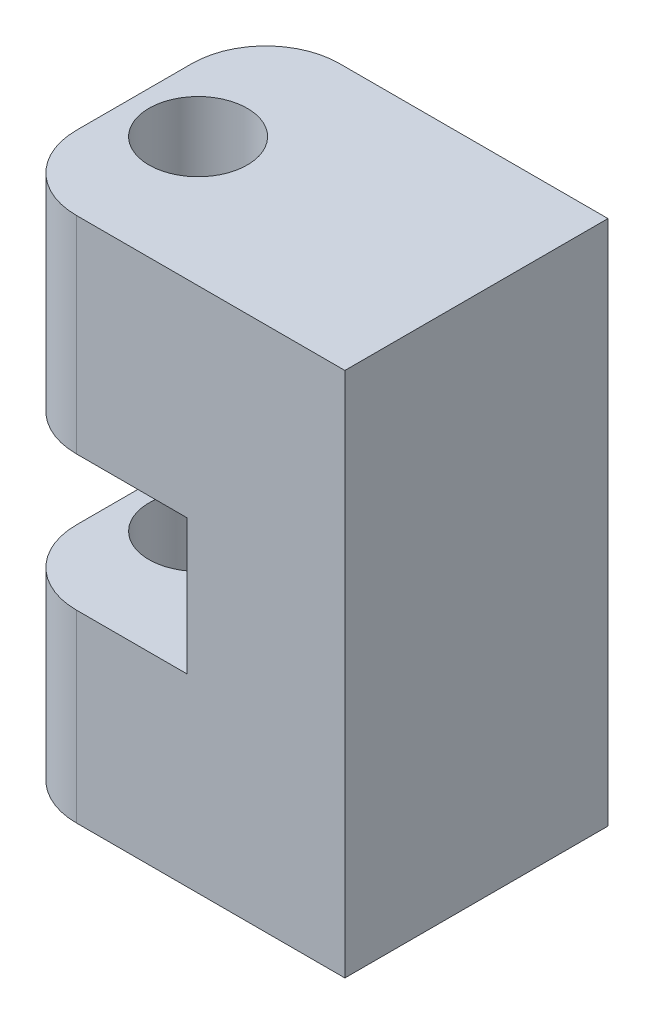
SolidWorks part; units mm, degrees
ref_plane "Front" through (0, 0, 0) normal (0, 0, 1) x (1, 0, 0)
ref_plane "Top" through (0, 0, 0) normal (0, 1, 0) x (1, 0, 0)
ref_plane "Right" through (0, 0, 0) normal (1, 0, 0) x (0, 0, -1)
sketch "Sketch1" plane through (0, 0, 0) normal (0, 1, 0) x (1, 0, 0)
  line L0 (0, 9.3172) -> (0, 9.1678) construction
  line L1 (0, 0) -> (20.32, 0)
  line L2 (0, 0) -> (0, 12.7)
  line L3 (0, 12.7) -> (20.32, 12.7)
  line L4 (20.32, 0) -> (20.32, 12.7)
  line L5 (0.0894, 9.3172) -> (0.0894, 9.1678)
  line L6 (-0.0894, 9.3172) -> (-0.0894, 9.1678)
  line L7 (0, 7.6957) -> (0, 5.0493) construction
  line L10 (5.1, 7.6957) -> (5.1, 5.0493)
  line L11 (-5.1, 7.6957) -> (-5.1, 5.0493)
  arc A0 (0.0894, 9.3172) -> (-0.0894, 9.3172) centre (0, 9.3172) ccw
  arc A1 (-0.0894, 9.1678) -> (0.0894, 9.1678) centre (0, 9.1678) ccw
  arc A4 (5.1, 7.6957) -> (-5.1, 7.6957) centre (0, 7.6957) ccw
  arc A5 (-5.1, 5.0493) -> (5.1, 5.0493) centre (0, 5.0493) ccw
  point P7 (0, 9.2425)
  point P14 (0, 6.3725)
  dimension "D1" = 20.32
  dimension "D2" = 12.7
extrude "Boss-Extrude4" add sketch "Sketch1" along normal blind 25.4 contours L11 A5 L1 L2 A1 L6 A0 L3 A4 | L1 A5 L10 A4 L3 L2 A0 L5 A1 | A5 L1 L4 L3 A4 L10
sketch "Sketch3" plane through (0, 25.4, 0) normal (0, 1, 0) x (1, 0, 0)
  circle A0 centre (0, 6.1634) radius 2
  dimension "D1" = 4
extrude "Cut-Extrude1" cut sketch "Sketch3" against normal blind 25.4 contours A0
sketch "Sketch5" plane through (20.32, 0, 0) normal (1, 0, 0) x (0, 0, -1)
  line L1 (38.2751, 38.8271) -> (-16.024, 38.8271)
  line L2 (38.2751, 38.8271) -> (38.2751, -55.3885)
  line L3 (38.2751, -55.3885) -> (-16.024, -55.3885)
  line L4 (-16.024, 38.8271) -> (-16.024, -55.3885)
extrude "Cut-Extrude2" cut sketch "Sketch5" against normal blind 4.5
sketch "Sketch7" plane through (-5.1, 0, 0) normal (-1, 0, 0) x (0, 0, 1)
  line L0 (-7.6957, 25.4) -> (-5.0493, 25.4) construction
  line L1 (-15.6651, 15) -> (3.0281, 15)
  line L2 (-15.6651, 15) -> (-15.6651, 9.5)
  line L3 (-15.6651, 9.5) -> (3.0281, 9.5)
  line L4 (3.0281, 15) -> (3.0281, 9.5)
  dimension "D1" = 5.5
  dimension "D2" = 10.4
extrude "Cut-Extrude3" cut sketch "Sketch7" against normal blind 14.5
sketch "Sketch9" plane through (0, 0, -12.7) normal (0, 0, -1) x (-1, 0, 0)
  line L1 (-22.5674, 28.7595) -> (13.5442, 28.7595)
  line L2 (-22.5674, 28.7595) -> (-22.5674, -4.4046)
  line L3 (-22.5674, -4.4046) -> (13.5442, -4.4046)
  line L4 (13.5442, 28.7595) -> (13.5442, -4.4046)
extrude "Cut-Extrude4" cut sketch "Sketch9" against normal blind 1
sketch "Sketch10" plane through (0, 0, 0) normal (0, 0, 1) x (1, 0, 0)
  line L1 (-28.2632, -7.6451) -> (34.5285, -7.6451)
  line L2 (-28.2632, -7.6451) -> (-28.2632, 29.5981)
  line L3 (-28.2632, 29.5981) -> (34.5285, 29.5981)
  line L4 (34.5285, -7.6451) -> (34.5285, 29.5981)
extrude "Cut-Extrude6" cut sketch "Sketch10" against normal blind 1
fillet "Fillet2" radius 3 4 edges at (-3.1005, 4.75, -1) (-3.1005, 20.2, -1) (-3.1585, 20.2, -11.7) (-3.1585, 4.75, -11.7)
sketch "Sketch11" plane through (9.4, 0, 0) normal (-1, 0, 0) x (0, 0, 1)
  line L1 (-11.7, 9.5) -> (-1, 9.5)
  line L2 (-11.7, 9.5) -> (-11.7, 15)
  line L3 (-11.7, 15) -> (-1, 15)
  line L4 (-1, 9.5) -> (-1, 15)
extrude "Boss-Extrude5" add sketch "Sketch11" along normal blind 2
sketch "Sketch12" plane through (-5.1, 0, 0) normal (-1, 0, 0) x (0, 0, 1)
  line L1 (-13.4183, -11.6019) -> (0, -11.6019)
  line L2 (-13.4183, -11.6019) -> (-13.4183, 44.9502)
  line L3 (-13.4183, 44.9502) -> (0, 44.9502)
  line L4 (0, -11.6019) -> (0, 44.9502)
extrude "Cut-Extrude7" cut sketch "Sketch12" against normal blind 10
sketch "Sketch14" plane through (7.4, 0, 0) normal (-1, 0, 0) x (0, 0, 1)
  line L1 (-11.7, 9.5) -> (-1, 9.5)
  line L2 (-11.7, 9.5) -> (-11.7, 15)
  line L3 (-11.7, 15) -> (-1, 15)
  line L4 (-1, 9.5) -> (-1, 15)
extrude "Boss-Extrude7" add sketch "Sketch14" along normal blind 2
sketch "Sketch15" plane through (4.9, 0, 0) normal (-1, 0, 0) x (0, 0, 1)
  line L1 (-11.7, 0) -> (-1, 0)
  line L2 (-11.7, 0) -> (-11.7, 9.5)
  line L3 (-11.7, 9.5) -> (-1, 9.5)
  line L4 (-1, 0) -> (-1, 9.5)
extrude "Boss-Extrude8" add sketch "Sketch15" along normal blind 6
sketch "Sketch16" plane through (4.9, 0, 0) normal (-1, 0, 0) x (0, 0, 1)
  line L1 (-11.7, 15) -> (-1, 15)
  line L2 (-11.7, 15) -> (-11.7, 25.4)
  line L3 (-11.7, 25.4) -> (-1, 25.4)
  line L4 (-1, 15) -> (-1, 25.4)
extrude "Boss-Extrude9" add sketch "Sketch16" along normal blind 6
fillet "Fillet3" radius 3 4 edges at (-1.1, 20.2, -1) (-1.1, 20.2, -11.7) (-1.1, 4.75, -11.7) (-1.1, 4.75, -1)
sketch "Sketch18" plane through (5.4, 0, 0) normal (-1, 0, 0) x (0, 0, 1)
  line L1 (-11.7, 15) -> (-1, 15)
  line L2 (-11.7, 15) -> (-11.7, 9.5)
  line L3 (-11.7, 9.5) -> (-1, 9.5)
  line L4 (-1, 15) -> (-1, 9.5)
extrude "Cut-Extrude8" cut sketch "Sketch18" against normal blind 1
sketch "Sketch21" plane through (15.82, 0, 0) normal (1, 0, 0) x (0, 0, -1)
  line L1 (-13.6512, 30.6954) -> (22.1459, 30.6954)
  line L2 (-13.6512, 30.6954) -> (-13.6512, -4.5948)
  line L3 (-13.6512, -4.5948) -> (22.1459, -4.5948)
  line L4 (22.1459, 30.6954) -> (22.1459, -4.5948)
extrude "Cut-Extrude9" cut sketch "Sketch21" against normal blind 3
sketch "Sketch22" plane through (0, 25.4, 0) normal (0, 1, 0) x (1, 0, 0)
  line L1 (-8.3333, 22.5284) -> (17.604, 22.5284)
  line L2 (-8.3333, 22.5284) -> (-8.3333, -13.9298)
  line L3 (-8.3333, -13.9298) -> (17.604, -13.9298)
  line L4 (17.604, 22.5284) -> (17.604, -13.9298)
extrude "Cut-Extrude10" cut sketch "Sketch22" against normal blind 2
sketch "Sketch23" plane through (0, 0, 0) normal (0, -1, 0) x (1, 0, 0)
  line L1 (-6.2486, 12.1341) -> (24.9701, 12.1341)
  line L2 (-6.2486, 12.1341) -> (-6.2486, -25.7385)
  line L3 (-6.2486, -25.7385) -> (24.9701, -25.7385)
  line L4 (24.9701, 12.1341) -> (24.9701, -25.7385)
extrude "Cut-Extrude11" cut sketch "Sketch23" against normal blind 2
sketch "Sketch24" plane through (0, 2, 0) normal (0, -1, 0) x (1, 0, 0)
  line L0 (-1.1, -4) -> (-1.1, -8.7) construction
  line L2 (12.82, -1) -> (1.9, -1) construction
  circle A0 centre (1.6, -6.25) radius 2
  dimension "D1" = 4
  dimension "D2" = 2.7
  dimension "D3" = 5.25
extrude "Cut-Extrude12" cut sketch "Sketch24" against normal blind 24
